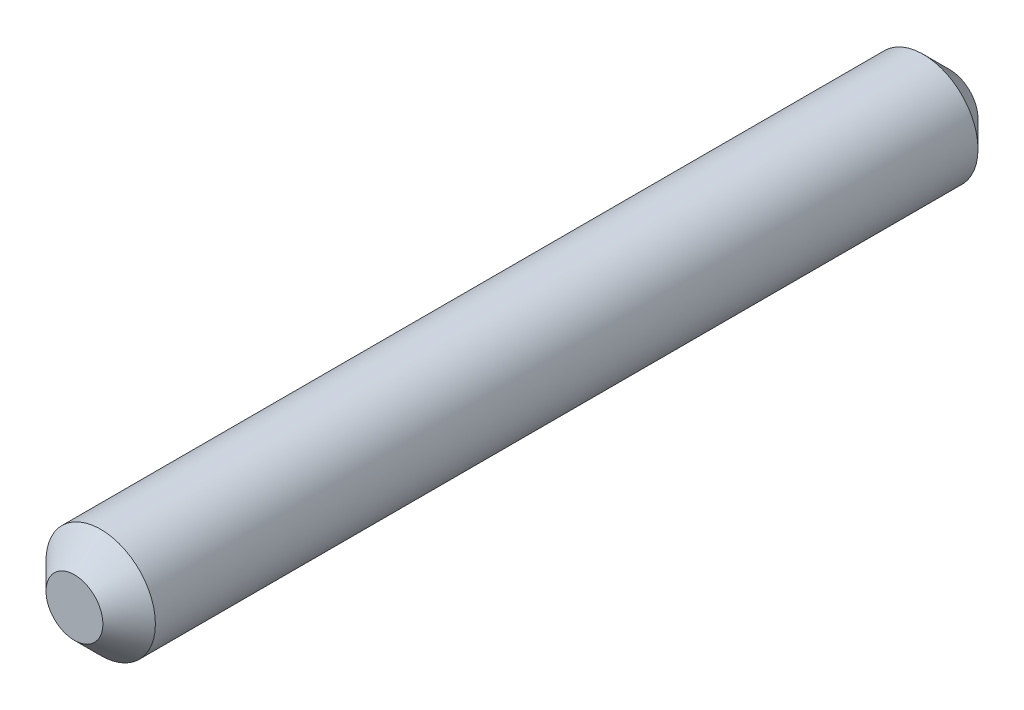
SolidWorks part; units mm, degrees
ref_plane "Front Plane" through (0, 0, 0) normal (0, 0, 1) x (1, 0, 0)
ref_plane "Top Plane" through (0, 0, 0) normal (0, 1, 0) x (1, 0, 0)
ref_plane "Right Plane" through (0, 0, 0) normal (1, 0, 0) x (0, 0, -1)
sketch "Sketch1" plane through (0, 0, 0) normal (0, 0, 1) x (1, 0, 0)
  circle A0 centre (0, 0) radius 1.5875
  dimension "D1" = 3.175
extrude "Boss-Extrude1" add sketch "Sketch1" along normal blind 25.4
chamfer "Chamfer2" distance 0.762 2 edges at (1.5875, 0, 25.4) (1.5875, 0, 0)
